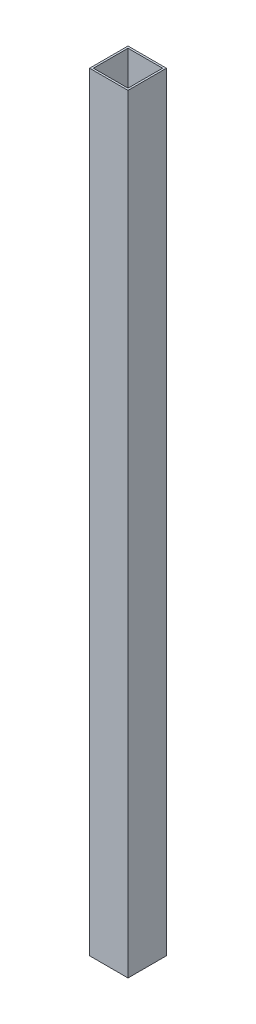
SolidWorks part; units mm, degrees
ref_plane "Front Plane" through (0, 0, 0) normal (0, 0, 1) x (1, 0, 0)
ref_plane "Top Plane" through (0, 0, 0) normal (0, 1, 0) x (1, 0, 0)
ref_plane "Right Plane" through (0, 0, 0) normal (1, 0, 0) x (0, 0, -1)
sketch "Sketch1" plane through (0, 0, 0) normal (0, 1, 0) x (1, 0, 0)
  line L0 (0, 0) -> (0, 25.4)
  line L1 (0, 25.4) -> (25.4, 25.4)
  line L2 (25.4, 25.4) -> (25.4, 0)
  line L3 (25.4, 0) -> (0, 0)
  line L6 (1.27, 12.3615) -> (1.27, 24.13)
  line L7 (1.27, 24.13) -> (12.7, 24.13)
  line L10 (12.7, 24.13) -> (24.13, 24.13)
  line L11 (24.13, 24.13) -> (24.13, 12.7)
  line L12 (24.13, 1.27) -> (24.13, 12.7)
  line L13 (24.13, 1.27) -> (12.7, 1.27)
  line L14 (1.27, 1.27) -> (12.7, 1.27)
  line L15 (1.27, 12.3615) -> (1.27, 1.27)
  dimension "D1" = 25.4
  dimension "D2" = 25.4
  dimension "D3" = 11.7685
  dimension "D4" = 11.0915
  dimension "D5" = 11.43
  dimension "D6" = 11.43
extrude "Boss-Extrude1" add sketch "Sketch1" along normal blind 508
sketch "Sketch2" plane through (0, 0, 0) normal (0, 0, 1) x (1, 0, 0)
  line L0 (12.7, 508) -> (12.7, 482.6) construction
  line L1 (0, 508) -> (25.4, 508) construction
  point P4 (0, 0)
